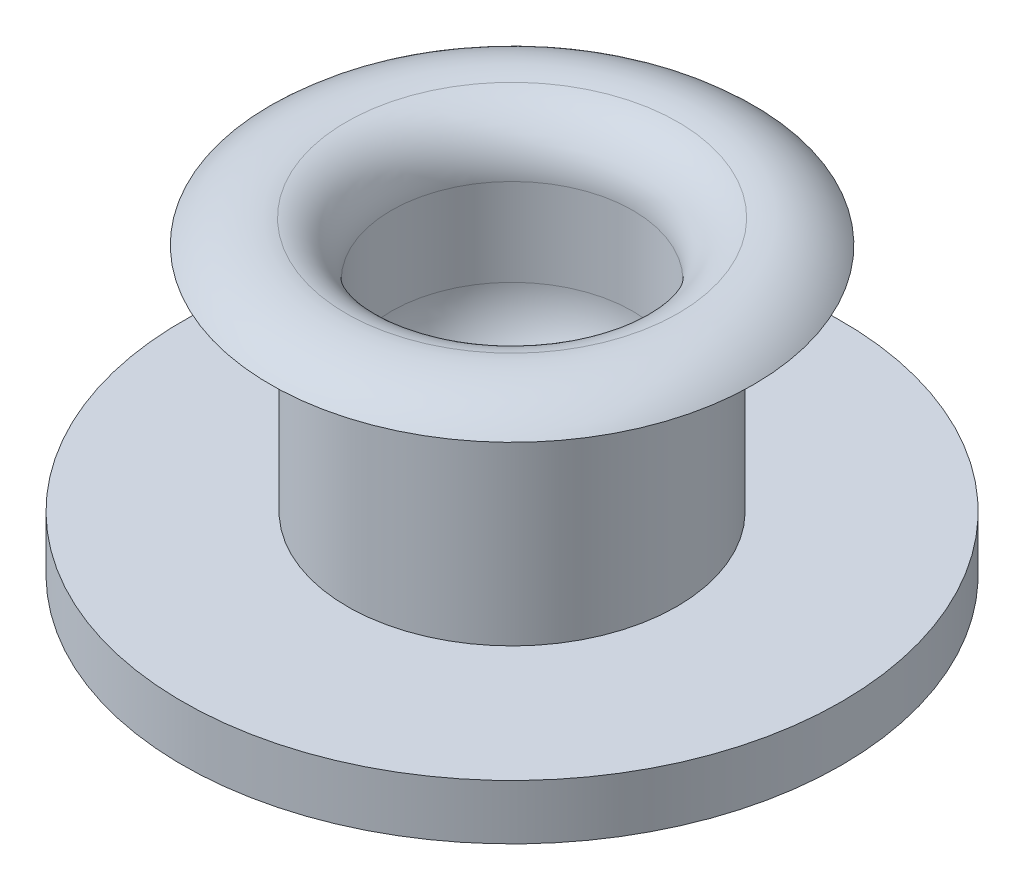
SolidWorks part; units mm, degrees
ref_plane "前视基准面" through (0, 0, 0) normal (0, 0, 1) x (1, 0, 0)
ref_plane "上视基准面" through (0, 0, 0) normal (0, 1, 0) x (1, 0, 0)
ref_plane "右视基准面" through (0, 0, 0) normal (1, 0, 0) x (0, 0, -1)
sketch "Sketch1" plane through (0, 0, 0) normal (0, 0, 1) x (1, 0, 0)
  line L0 (-1.5, 1) -> (-2.2, 1)
  line L1 (0, -1.1) -> (-1.5, -1.1)
  line L2 (0, -1.1) -> (0, 1) construction
  line L3 (0, 1) -> (-1.5, 1) construction
  line L4 (-1.5, -1.1) -> (-1.5, 1)
  line L5 (-1.1, 1) -> (-1.1, -0.7621)
  line L6 (-1.1, -0.7621) -> (0, -0.925)
  line L7 (0, -0.925) -> (0, -1.1)
  line L8 (0, 0.7121) -> (-1.1, 0.7121) construction
  arc A0 (-2.2, 1) -> (-1.1, 1) centre (-1.65, 0.4495) cw
revolve "Revolve1" add sketch "Sketch1" angle 360 about L2
fillet "Fillet1" radius 0.8 1 edges at (1.1, -0.7621, 0)
fillet "Fillet2" radius 0.5 1 edges at (1.1, 1, 0)
sketch "Sketch2" plane through (0, -1.1, 0) normal (0, -1, 0) x (1, 0, 0)
  circle A0 centre (0, 0) radius 3
extrude "Boss-Extrude1" add sketch "Sketch2" along normal blind 0.5
